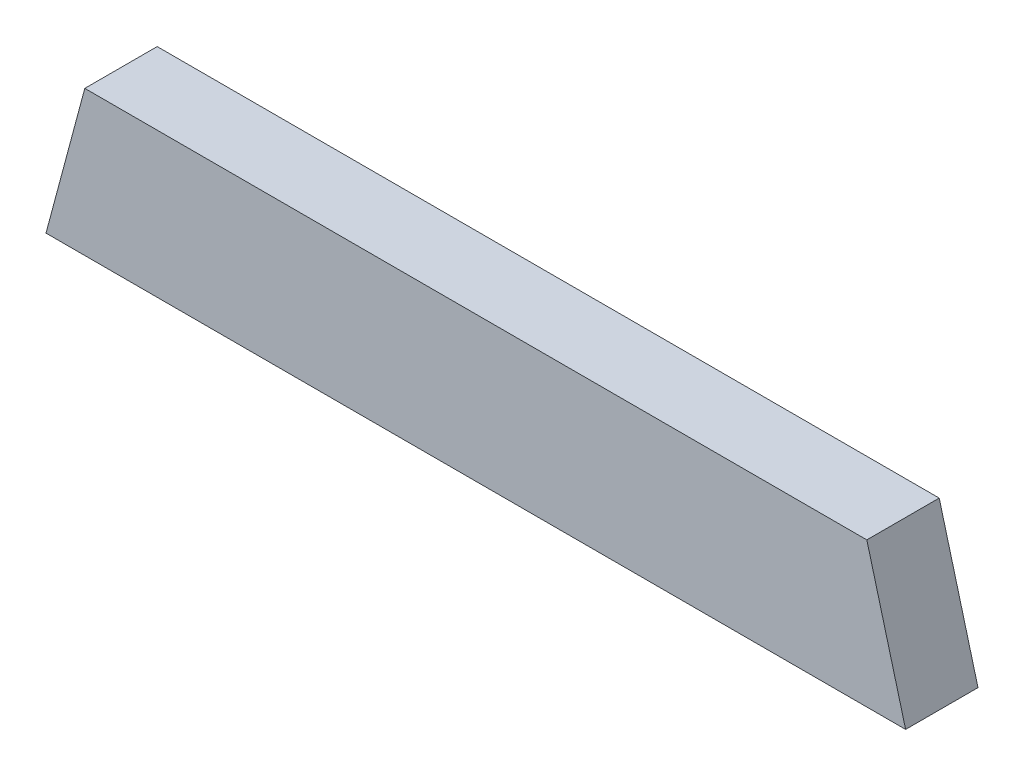
SolidWorks part; units mm, degrees
ref_plane "Front Plane" through (0, 0, 0) normal (0, 0, 1) x (1, 0, 0)
ref_plane "Top Plane" through (0, 0, 0) normal (0, 1, 0) x (1, 0, 0)
ref_plane "Right Plane" through (0, 0, 0) normal (1, 0, 0) x (0, 0, -1)
sketch "Sketch1" plane through (0, 0, 0) normal (0, 0, 1) x (1, 0, 0)
  line L0 (0, 0) -> (27.2236, 101.6)
  line L1 (0, 0) -> (603.25, 0)
  line L2 (0, 0) -> (0, 101.6)
  line L3 (0, 101.6) -> (603.25, 101.6)
  line L4 (603.25, 0) -> (603.25, 101.6)
  line L6 (603.25, 0) -> (576.0264, 101.6)
  dimension "D1" = 603.25
  dimension "D2" = 101.6
  dimension "D3" = 15
  dimension "D4" = 15
extrude "Boss-Extrude1" add sketch "Sketch1" along normal blind 50.8 contours L1 L6 L3 L0
